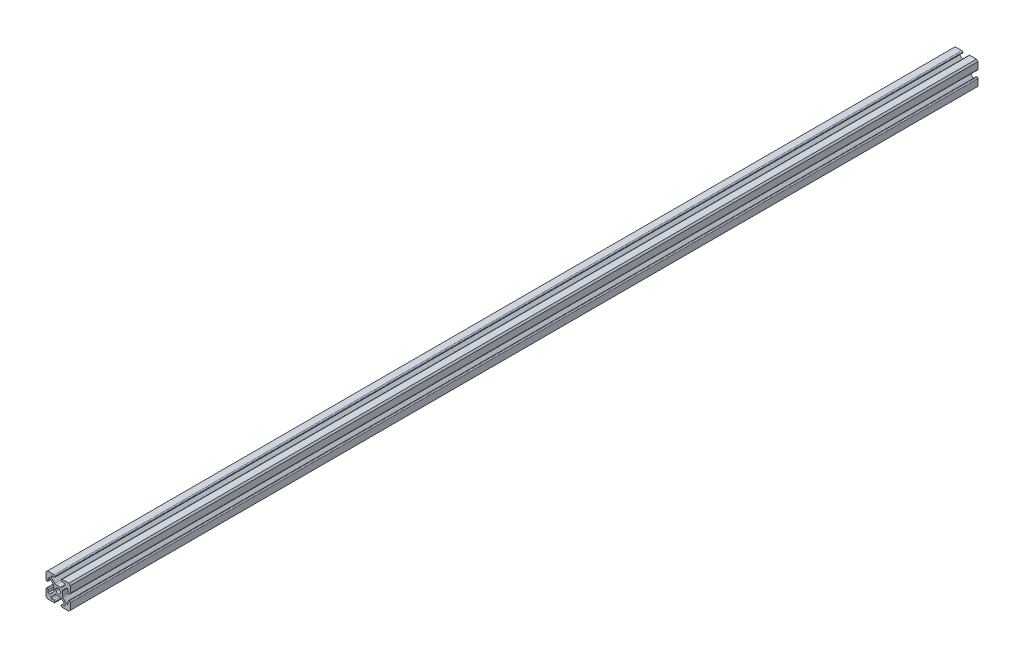
SolidWorks part; units mm, degrees
ref_plane "Front Plane" through (0, 0, 0) normal (0, 0, 1) x (1, 0, 0)
ref_plane "Top Plane" through (0, 0, 0) normal (0, 1, 0) x (1, 0, 0)
ref_plane "Right Plane" through (0, 0, 0) normal (1, 0, 0) x (0, 0, -1)
other "Configuration Table"
sketch "Sketch1" plane through (0, 0, 0) normal (0, 0, 1) x (1, 0, 0)
  line L0 (-11.2, -12.7) -> (-4.2223, -12.7)
  line L1 (-3.2063, -11.684) -> (-3.2063, -11.4407)
  line L2 (-4.2223, -10.4247) -> (-6.4093, -10.4247)
  line L3 (-7.1277, -8.6902) -> (-3.5932, -5.1557)
  line L4 (-2.0306, -4.5085) -> (2.0306, -4.5085)
  line L5 (3.5932, -5.1557) -> (7.1277, -8.6902)
  line L6 (6.4093, -10.4247) -> (4.2223, -10.4247)
  line L7 (3.2063, -11.4407) -> (3.2063, -11.684)
  line L8 (4.2223, -12.7) -> (11.2, -12.7)
  line L9 (11.2, -12.7) -> (12.7, -11.2)
  line L10 (12.7, -11.2) -> (12.7, -4.2223)
  line L11 (11.684, -3.2063) -> (11.4407, -3.2063)
  line L12 (10.4247, -4.2223) -> (10.4247, -6.4093)
  line L13 (8.6902, -7.1277) -> (5.1557, -3.5932)
  line L14 (4.5085, -2.0306) -> (4.5085, 2.0306)
  line L15 (5.1557, 3.5932) -> (8.6902, 7.1277)
  line L16 (10.4247, 6.4093) -> (10.4247, 4.2223)
  line L17 (11.4407, 3.2063) -> (11.684, 3.2063)
  line L18 (12.7, 4.2223) -> (12.7, 11.2)
  line L19 (12.7, 11.2) -> (11.2, 12.7)
  line L20 (11.2, 12.7) -> (4.2223, 12.7)
  line L21 (3.2063, 11.684) -> (3.2063, 11.4407)
  line L22 (4.2223, 10.4247) -> (6.4093, 10.4247)
  line L23 (7.1277, 8.6902) -> (3.5932, 5.1557)
  line L24 (2.0306, 4.5085) -> (-2.0306, 4.5085)
  line L25 (-3.5932, 5.1557) -> (-7.1277, 8.6902)
  line L26 (-6.4093, 10.4247) -> (-4.2223, 10.4247)
  line L27 (-3.2063, 11.4407) -> (-3.2063, 11.684)
  line L28 (-4.2223, 12.7) -> (-11.2, 12.7)
  line L29 (-11.2, 12.7) -> (-12.7, 11.2)
  line L30 (-12.7, 11.2) -> (-12.7, 4.2223)
  line L31 (-11.684, 3.2063) -> (-11.4407, 3.2063)
  line L32 (-10.4247, 4.2223) -> (-10.4247, 6.4093)
  line L33 (-8.6902, 7.1277) -> (-5.1557, 3.5932)
  line L34 (-4.5085, 2.0306) -> (-4.5085, -2.0306)
  line L35 (-5.1557, -3.5932) -> (-8.6902, -7.1277)
  line L36 (-10.4247, -6.4093) -> (-10.4247, -4.2223)
  line L37 (-11.4407, -3.2063) -> (-11.684, -3.2063)
  line L38 (-12.7, -4.2223) -> (-12.7, -11.2)
  line L39 (-12.7, -11.2) -> (-11.2, -12.7)
  arc A0 (-2.555, 0) -> (2.555, 0) centre (0, 0) ccw
  arc A1 (2.555, 0) -> (-2.555, 0) centre (0, 0) ccw
  arc A2 (-4.2223, -12.7) -> (-3.2063, -11.684) centre (-4.2223, -11.684) ccw
  arc A3 (-3.2063, -11.4407) -> (-4.2223, -10.4247) centre (-4.2223, -11.4407) ccw
  arc A4 (-7.1277, -8.6902) -> (-6.4093, -10.4247) centre (-6.4093, -9.4087) ccw
  arc A5 (-2.0306, -4.5085) -> (-3.5932, -5.1557) centre (-2.0306, -6.7183) ccw
  arc A6 (3.5932, -5.1557) -> (2.0306, -4.5085) centre (2.0306, -6.7183) ccw
  arc A7 (7.4253, -9.4087) -> (7.1277, -8.6902) centre (6.4093, -9.4087) ccw
  arc A8 (6.4093, -10.4247) -> (7.4253, -9.4087) centre (6.4093, -9.4087) ccw
  arc A9 (4.2223, -10.4247) -> (3.2063, -11.4407) centre (4.2223, -11.4407) ccw
  arc A10 (3.2063, -11.684) -> (4.2223, -12.7) centre (4.2223, -11.684) ccw
  arc A11 (12.7, -4.2223) -> (11.684, -3.2063) centre (11.684, -4.2223) ccw
  arc A12 (11.4407, -3.2063) -> (10.4247, -4.2223) centre (11.4407, -4.2223) ccw
  arc A13 (8.6902, -7.1277) -> (10.4247, -6.4093) centre (9.4087, -6.4093) ccw
  arc A14 (4.5085, -2.0306) -> (5.1557, -3.5932) centre (6.7183, -2.0306) ccw
  arc A15 (5.1557, 3.5932) -> (4.5085, 2.0306) centre (6.7183, 2.0306) ccw
  arc A16 (9.4087, 7.4253) -> (8.6902, 7.1277) centre (9.4087, 6.4093) ccw
  arc A17 (10.4247, 6.4093) -> (9.4087, 7.4253) centre (9.4087, 6.4093) ccw
  arc A18 (10.4247, 4.2223) -> (11.4407, 3.2063) centre (11.4407, 4.2223) ccw
  arc A19 (11.684, 3.2063) -> (12.7, 4.2223) centre (11.684, 4.2223) ccw
  arc A20 (4.2223, 12.7) -> (3.2063, 11.684) centre (4.2223, 11.684) ccw
  arc A21 (3.2063, 11.4407) -> (4.2223, 10.4247) centre (4.2223, 11.4407) ccw
  arc A22 (7.1277, 8.6902) -> (6.4093, 10.4247) centre (6.4093, 9.4087) ccw
  arc A23 (2.0306, 4.5085) -> (3.5932, 5.1557) centre (2.0306, 6.7183) ccw
  arc A24 (-3.5932, 5.1557) -> (-2.0306, 4.5085) centre (-2.0306, 6.7183) ccw
  arc A25 (-7.4253, 9.4087) -> (-7.1277, 8.6902) centre (-6.4093, 9.4087) ccw
  arc A26 (-6.4093, 10.4247) -> (-7.4253, 9.4087) centre (-6.4093, 9.4087) ccw
  arc A27 (-4.2223, 10.4247) -> (-3.2063, 11.4407) centre (-4.2223, 11.4407) ccw
  arc A28 (-3.2063, 11.684) -> (-4.2223, 12.7) centre (-4.2223, 11.684) ccw
  arc A29 (-12.7, 4.2223) -> (-11.684, 3.2063) centre (-11.684, 4.2223) ccw
  arc A30 (-11.4407, 3.2063) -> (-10.4247, 4.2223) centre (-11.4407, 4.2223) ccw
  arc A31 (-8.6902, 7.1277) -> (-10.4247, 6.4093) centre (-9.4087, 6.4093) ccw
  arc A32 (-4.5085, 2.0306) -> (-5.1557, 3.5932) centre (-6.7183, 2.0306) ccw
  arc A33 (-5.1557, -3.5932) -> (-4.5085, -2.0306) centre (-6.7183, -2.0306) ccw
  arc A34 (-9.4087, -7.4253) -> (-8.6902, -7.1277) centre (-9.4087, -6.4093) ccw
  arc A35 (-10.4247, -6.4093) -> (-9.4087, -7.4253) centre (-9.4087, -6.4093) ccw
  arc A36 (-10.4247, -4.2223) -> (-11.4407, -3.2063) centre (-11.4407, -4.2223) ccw
  arc A37 (-11.684, -3.2063) -> (-12.7, -4.2223) centre (-11.684, -4.2223) ccw
extrude "Boss-Extrude1" add sketch "Sketch1" along normal blind 950
equation "\"Extrusion Length\"= 24"
